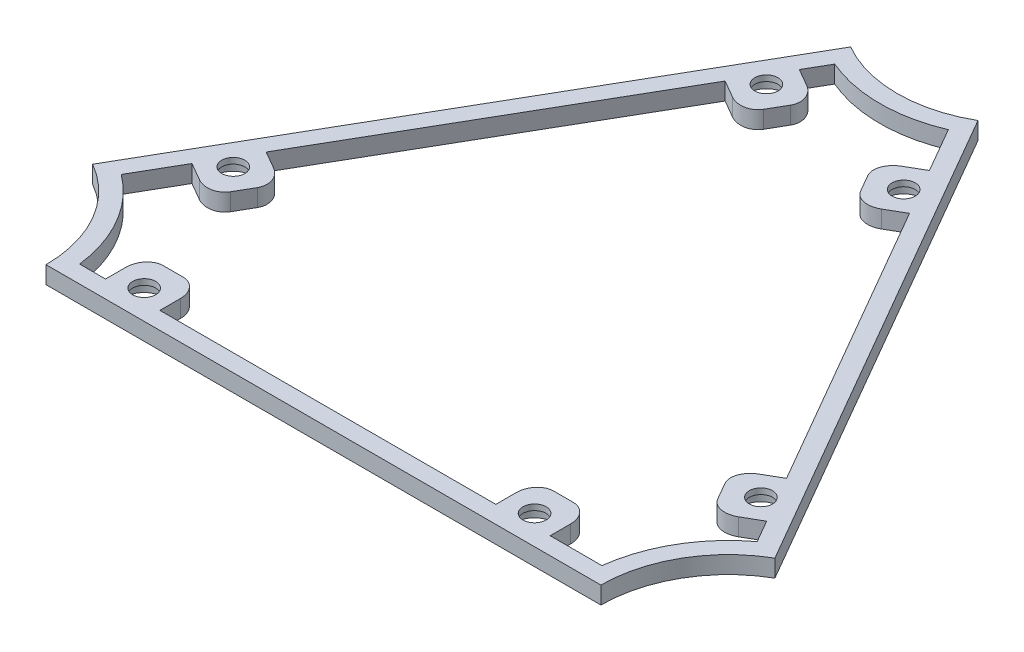
SolidWorks part; units mm, degrees
ref_plane "Front Plane" through (0, 0, 0) normal (0, 0, 1) x (1, 0, 0)
ref_plane "Top Plane" through (0, 0, 0) normal (0, 1, 0) x (1, 0, 0)
ref_plane "Right Plane" through (0, 0, 0) normal (1, 0, 0) x (0, 0, -1)
sketch "Sketch2" plane through (0, 0, 0) normal (0, 1, 0) x (1, 0, 0)
  line L0 (14.3085, 50.0901) -> (16.9066, 51.5901) construction
  line L6 (-40.7, -37.4366) -> (-40.7, -33.9007) construction
  line L12 (-37.7, -30.4366) -> (-34.3, -30.4366) construction
  line L14 (50.9526, -29.4175) -> (48.3545, -27.9175) construction
  line L17 (-31.3, -33.9007) -> (-31.3, -37.4366) construction
  line L20 (0, 55.8349) -> (0, 58.8349) construction
  line L22 (-48.3545, -27.9175) -> (-50.9526, -29.4175) construction
  line L28 (-31.3, -37.4366) -> (-19.525, -37.4366) construction
  line L32 (-19.525, -40.4366) -> (-48, -40.4366) construction
  line L37 (-48, -37.4366) -> (-40.7, -37.4366) construction
  line L44 (26.825, -37.4366) -> (26.825, -33.9007) construction
  line L46 (29.825, -30.4366) -> (33.225, -30.4366) construction
  line L48 (36.225, -33.9007) -> (36.225, -37.4366) construction
  line L49 (36.225, -37.4366) -> (48, -37.4366) construction
  line L51 (48, -40.4366) -> (19.525, -40.4366) construction
  line L53 (19.525, -37.4366) -> (26.825, -37.4366) construction
  line L54 (52.771, -16.5289) -> (49.7088, -18.2969) construction
  line L55 (45.2088, -17.4309) -> (43.5088, -14.4864) construction
  line L56 (45.0088, -10.1563) -> (48.071, -8.3883) construction
  line L57 (48.071, -8.3883) -> (42.1835, 1.8091) construction
  line L59 (44.7816, 3.3091) -> (59.0191, -21.3509) construction
  line L61 (56.421, -22.8509) -> (52.771, -16.5289) construction
  line L62 (11.4463, 41.0475) -> (9.7463, 43.992) construction
  line L63 (11.2463, 48.3221) -> (14.3085, 50.0901) construction
  line L64 (14.3085, 50.0901) -> (8.421, 60.2875) construction
  line L66 (11.0191, 61.7875) -> (25.2566, 37.1274) construction
  line L68 (22.6585, 35.6274) -> (19.0085, 41.9494) construction
  line L69 (19.0085, 41.9494) -> (15.9463, 40.1815) construction
  line L70 (-12.071, 53.9655) -> (-9.0088, 52.1976) construction
  line L71 (-7.5088, 47.8674) -> (-9.2088, 44.923) construction
  line L72 (-13.7088, 44.0569) -> (-16.771, 45.8249) construction
  line L73 (-16.771, 45.8249) -> (-22.6585, 35.6274) construction
  line L75 (-25.2566, 37.1274) -> (-11.0191, 61.7875) construction
  line L77 (-8.421, 60.2875) -> (-12.071, 53.9655) construction
  line L78 (-45.8335, -4.5128) -> (-42.7713, -6.2808) construction
  line L79 (-41.2713, -10.6109) -> (-42.9713, -13.5554) construction
  line L80 (-47.4713, -14.4214) -> (-50.5335, -12.6535) construction
  line L81 (-50.5335, -12.6535) -> (-56.421, -22.8509) construction
  line L83 (-59.0191, -21.3509) -> (-44.7816, 3.3091) construction
  line L85 (-42.1835, 1.8091) -> (-45.8335, -4.5128) construction
  line L86 (-40.7, -37.4366) -> (-40.7, -33.9007)
  line L87 (-37.7, -30.4366) -> (-34.3, -30.4366)
  line L88 (-31.3, -33.9007) -> (-31.3, -37.4366)
  line L89 (-31.3, -37.4366) -> (-19.525, -37.4366)
  line L91 (-19.525, -40.4366) -> (-48, -40.4366)
  line L93 (-45.1804, -37.4366) -> (-40.7, -37.4366)
  line L94 (26.825, -37.4366) -> (26.825, -33.9007)
  line L95 (29.825, -30.4366) -> (33.225, -30.4366)
  line L96 (36.225, -33.9007) -> (36.225, -37.4366)
  line L97 (36.225, -37.4366) -> (45.1804, -37.4366)
  line L99 (48, -40.4366) -> (19.525, -40.4366)
  line L101 (19.525, -37.4366) -> (26.825, -37.4366)
  line L102 (52.771, -16.5289) -> (49.7088, -18.2969)
  line L103 (45.2088, -17.4309) -> (43.5088, -14.4864)
  line L104 (45.0088, -10.1563) -> (48.071, -8.3883)
  line L105 (48.071, -8.3883) -> (42.1835, 1.8091)
  line L107 (44.7816, 3.3091) -> (59.0191, -21.3509)
  line L109 (55.0112, -20.4091) -> (52.771, -16.5289)
  line L110 (11.4463, 41.0475) -> (9.7463, 43.992)
  line L111 (11.2463, 48.3221) -> (14.3085, 50.0901)
  line L112 (14.3085, 50.0901) -> (9.8308, 57.8456)
  line L114 (11.0191, 61.7875) -> (25.2566, 37.1274)
  line L116 (22.6585, 35.6274) -> (19.0085, 41.9494)
  line L117 (19.0085, 41.9494) -> (15.9463, 40.1815)
  line L118 (-12.071, 53.9655) -> (-9.0088, 52.1976)
  line L119 (-7.5088, 47.8674) -> (-9.2088, 44.923)
  line L120 (-13.7088, 44.0569) -> (-16.771, 45.8249)
  line L121 (-16.771, 45.8249) -> (-22.6585, 35.6274)
  line L123 (-25.2566, 37.1274) -> (-11.0191, 61.7875)
  line L125 (-9.8308, 57.8456) -> (-12.071, 53.9655)
  line L126 (-45.8335, -4.5128) -> (-42.7713, -6.2808)
  line L127 (-41.2713, -10.6109) -> (-42.9713, -13.5554)
  line L128 (-47.4713, -14.4214) -> (-50.5335, -12.6535)
  line L129 (-50.5335, -12.6535) -> (-55.0112, -20.4091)
  line L131 (-59.0191, -21.3509) -> (-44.7816, 3.3091)
  line L133 (-42.1835, 1.8091) -> (-45.8335, -4.5128)
  line L134 (-19.525, -40.4366) -> (19.525, -40.4366)
  line L135 (19.525, -37.4366) -> (-19.525, -37.4366)
  line L136 (-44.7816, 3.3091) -> (-25.2566, 37.1274)
  line L137 (-22.6585, 35.6274) -> (-42.1835, 1.8091)
  line L138 (22.6585, 35.6274) -> (42.1835, 1.8091)
  line L139 (44.7816, 3.3091) -> (25.2566, 37.1274)
  arc A0 (59.0191, -21.3509) -> (48, -40.4366) centre (70.0382, -40.4366) ccw
  arc A1 (55.0112, -20.4091) -> (45.1804, -37.4366) centre (70.0382, -40.4366) ccw
  arc A2 (11.0191, 61.7875) -> (-11.0191, 61.7875) centre (0, 80.8731) cw
  arc A3 (9.8308, 57.8456) -> (-9.8308, 57.8456) centre (0, 80.8731) cw
  arc A4 (-45.1804, -37.4366) -> (-55.0112, -20.4091) centre (-70.0382, -40.4366) ccw
  arc A5 (-48, -40.4366) -> (-59.0191, -21.3509) centre (-70.0382, -40.4366) ccw
  ellipse E0 centre (-37.7, -33.9007) end of major axis (-37.7, -30.4366) minor radius 3 (-37.7, -30.4366) -> (-40.7, -33.9007) ccw construction
  ellipse E1 centre (-34.3, -33.9007) end of major axis (-34.3, -30.4366) minor radius 3 (-31.3, -33.9007) -> (-34.3, -30.4366) ccw construction
  ellipse E2 centre (29.825, -33.9007) end of major axis (29.825, -37.3648) minor radius 3 (29.825, -30.4366) -> (26.825, -33.9007) ccw construction
  ellipse E3 centre (33.225, -33.9007) end of major axis (33.225, -37.3648) minor radius 3 (36.225, -33.9007) -> (33.225, -30.4366) ccw construction
  ellipse E4 centre (48.2088, -15.6988) end of major axis (51.2088, -13.9668) minor radius 3 (45.2088, -17.4309) -> (49.7088, -18.2969) ccw construction
  ellipse E5 centre (46.5088, -12.7543) end of major axis (43.5088, -14.4864) minor radius 3 (45.0088, -10.1563) -> (43.5088, -14.4864) ccw construction
  ellipse E6 centre (12.7463, 45.724) end of major axis (9.7463, 43.992) minor radius 3 (11.2463, 48.3221) -> (9.7463, 43.992) ccw construction
  ellipse E7 centre (14.4463, 42.7795) end of major axis (17.4463, 44.5116) minor radius 3 (11.4463, 41.0475) -> (15.9463, 40.1815) ccw construction
  ellipse E8 centre (-10.5088, 49.5995) end of major axis (-7.5088, 47.8674) minor radius 3 (-7.5088, 47.8674) -> (-9.0088, 52.1976) ccw construction
  ellipse E9 centre (-12.2088, 46.655) end of major axis (-9.2088, 44.923) minor radius 3 (-13.7088, 44.0569) -> (-9.2088, 44.923) ccw construction
  ellipse E10 centre (-44.2713, -8.8789) end of major axis (-41.2713, -10.6109) minor radius 3 (-41.2713, -10.6109) -> (-42.7713, -6.2808) ccw construction
  ellipse E11 centre (-45.9713, -11.8234) end of major axis (-48.9713, -10.0913) minor radius 3 (-47.4713, -14.4214) -> (-42.9713, -13.5554) ccw construction
  ellipse E12 centre (-37.7, -33.9007) end of major axis (-37.7, -30.4366) minor radius 3 (-37.7, -30.4366) -> (-40.7, -33.9007) ccw
  ellipse E13 centre (-34.3, -33.9007) end of major axis (-34.3, -30.4366) minor radius 3 (-31.3, -33.9007) -> (-34.3, -30.4366) ccw
  ellipse E14 centre (29.825, -33.9007) end of major axis (29.825, -37.3648) minor radius 3 (29.825, -30.4366) -> (26.825, -33.9007) ccw
  ellipse E15 centre (33.225, -33.9007) end of major axis (33.225, -37.3648) minor radius 3 (36.225, -33.9007) -> (33.225, -30.4366) ccw
  ellipse E16 centre (48.2088, -15.6988) end of major axis (45.2088, -17.4309) minor radius 3 (45.2088, -17.4309) -> (49.7088, -18.2969) ccw
  ellipse E17 centre (46.5088, -12.7543) end of major axis (43.5088, -14.4864) minor radius 3 (45.0088, -10.1563) -> (43.5088, -14.4864) ccw
  ellipse E18 centre (12.7463, 45.724) end of major axis (15.7463, 47.4561) minor radius 3 (11.2463, 48.3221) -> (9.7463, 43.992) ccw
  ellipse E19 centre (14.4463, 42.7795) end of major axis (17.4463, 44.5116) minor radius 3 (11.4463, 41.0475) -> (15.9463, 40.1815) ccw
  ellipse E20 centre (-10.5088, 49.5995) end of major axis (-7.5088, 47.8674) minor radius 3 (-7.5088, 47.8674) -> (-9.0088, 52.1976) ccw
  ellipse E21 centre (-12.2088, 46.655) end of major axis (-9.2088, 44.923) minor radius 3 (-13.7088, 44.0569) -> (-9.2088, 44.923) ccw
  ellipse E22 centre (-44.2713, -8.8789) end of major axis (-47.2713, -7.1468) minor radius 3 (-41.2713, -10.6109) -> (-42.7713, -6.2808) ccw
  ellipse E23 centre (-45.9713, -11.8234) end of major axis (-48.9713, -10.0913) minor radius 3 (-47.4713, -14.4214) -> (-42.9713, -13.5554) ccw
extrude "Boss-Extrude2" add sketch "Sketch2" along normal blind 3
sketch "Sketch3" plane through (0, 3, 0) normal (0, 1, 0) x (1, 0, 0)
  circle A1 centre (31.525, -35.4366) radius 2
  circle A2 centre (-36, -35.4526) radius 2 construction
  circle A4 centre (48.7028, -13.4506) radius 2 construction
  circle A6 centre (-12.7028, 48.9032) radius 2 construction
  circle A7 centre (-36, -35.4526) radius 2
  circle A8 centre (-46.4515, -9.5832) radius 2
  circle A9 centre (48.7028, -13.4506) radius 2
  circle A10 centre (14.9265, 45.0197) radius 2
  circle A11 centre (-12.7028, 48.9032) radius 2
  arc A12 (-44.7194, -10.5832) -> (-48.1835, -8.5832) centre (-46.4515, -9.5832) ccw construction
  arc A13 (31.525, -33.4366) -> (31.525, -37.4366) centre (31.525, -35.4366) ccw construction
  arc A14 (13.1944, 44.0197) -> (16.6585, 46.0197) centre (14.9265, 45.0197) ccw construction
extrude "Cut-Extrude1" cut sketch "Sketch3" against normal through all
sketch "Sketch4" plane through (0, 0, 0) normal (0, -1, 0) x (1, 0, 0)
  line L0 (47.495, 17.9585) -> (53.2107, 14.6585)
  line L1 (-39.3, 32.1526) -> (-32.7, 32.1526)
  line L2 (-39.3, 32.1526) -> (-39.3, 38.7526)
  line L3 (-39.3, 38.7526) -> (-32.7, 38.7526)
  line L4 (-32.7, 32.1526) -> (-32.7, 38.7526)
  line L5 (-39.3, 32.1526) -> (-32.7, 38.7526) construction
  line L6 (-39.3, 38.7526) -> (-32.7, 32.1526) construction
  line L7 (34.841, 32.1205) -> (28.209, 32.1205)
  line L8 (34.841, 32.1205) -> (34.841, 38.7526)
  line L9 (34.841, 38.7526) -> (28.209, 38.7526)
  line L10 (28.209, 32.1205) -> (28.209, 38.7526)
  line L11 (34.841, 32.1205) -> (28.209, 38.7526) construction
  line L12 (34.841, 38.7526) -> (28.209, 32.1205) construction
  line L13 (47.495, 17.9585) -> (44.195, 12.2427)
  line L14 (44.195, 12.2427) -> (49.9107, 8.9427)
  line L15 (53.2107, 14.6585) -> (49.9107, 8.9427)
  line L16 (13.7127, -40.49) -> (19.4562, -43.806)
  line L17 (10.3967, -46.2335) -> (13.7127, -40.49)
  line L18 (10.3967, -46.2335) -> (16.1402, -49.5495)
  line L19 (16.1402, -49.5495) -> (19.4562, -43.806)
  line L20 (-8.195, -50.1111) -> (-13.9107, -53.4111)
  line L21 (-8.195, -50.1111) -> (-11.495, -44.3953)
  line L22 (-11.495, -44.3953) -> (-17.2107, -47.6953)
  line L23 (-13.9107, -53.4111) -> (-17.2107, -47.6953)
  line L24 (-41.9217, 8.3694) -> (-47.6652, 5.0534)
  line L25 (-45.2377, 14.1129) -> (-41.9217, 8.3694)
  line L26 (-45.2377, 14.1129) -> (-50.9812, 10.7969)
  line L27 (-50.9812, 10.7969) -> (-47.6652, 5.0534)
  point P0 (-36, 35.4526)
  point P6 (31.525, 35.4366)
  point P30 (0, 0)
  dimension "D1" = 6.6
  dimension "D2" = 3
extrude "Cut-Extrude2" [suppressed] cut sketch "Sketch4" against normal blind 2
sketch "Sketch5" plane through (0, 0, 0) normal (0, -1, 0) x (1, 0, 0)
  circle A0 centre (48.7028, 13.4506) radius 3.3
  circle A1 centre (31.525, 35.4366) radius 3.3
  circle A2 centre (-12.7028, -48.9032) radius 3.3
  circle A3 centre (14.9265, -45.0197) radius 3.3
  circle A4 centre (-36, 35.4526) radius 3.3
  circle A5 centre (-46.4515, 9.5832) radius 3.3
  point P20 (0, 0)
  dimension "D1" = 6.6
  dimension "D2" = 3
extrude "Cut-Extrude3" cut sketch "Sketch5" against normal offset from surface (2 mm away) 1 up to face at (-12.7028, 3, -46.9032)
